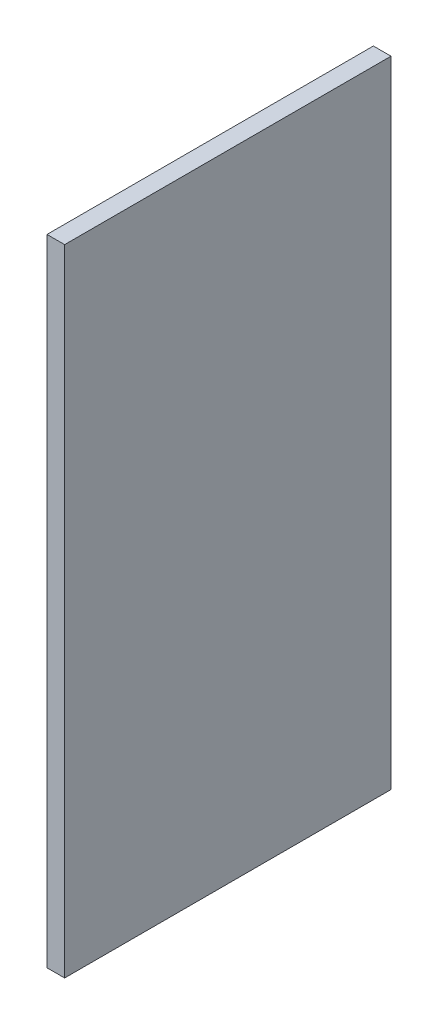
SolidWorks part; units mm, degrees
ref_plane "Front Plane" through (0, 0, 0) normal (0, 0, 1) x (1, 0, 0)
ref_plane "Top Plane" through (0, 0, 0) normal (0, 1, 0) x (1, 0, 0)
ref_plane "Right Plane" through (0, 0, 0) normal (1, 0, 0) x (0, 0, -1)
sketch "Sketch1" plane through (0, 25.4, 0) normal (0, 1, 0) x (1, 0, 0)
  line L0 (-304.8, -127) -> (304.8, -127) construction
  line L1 (304.8, 107.95) -> (292.1, 107.95)
  line L2 (304.8, 107.95) -> (304.8, -127)
  line L3 (304.8, -127) -> (292.1, -127)
  line L4 (292.1, 107.95) -> (292.1, -127)
  dimension "D1" = 12.7
extrude "Boss-Extrude1" add sketch "Sketch1" along normal blind 457.2
